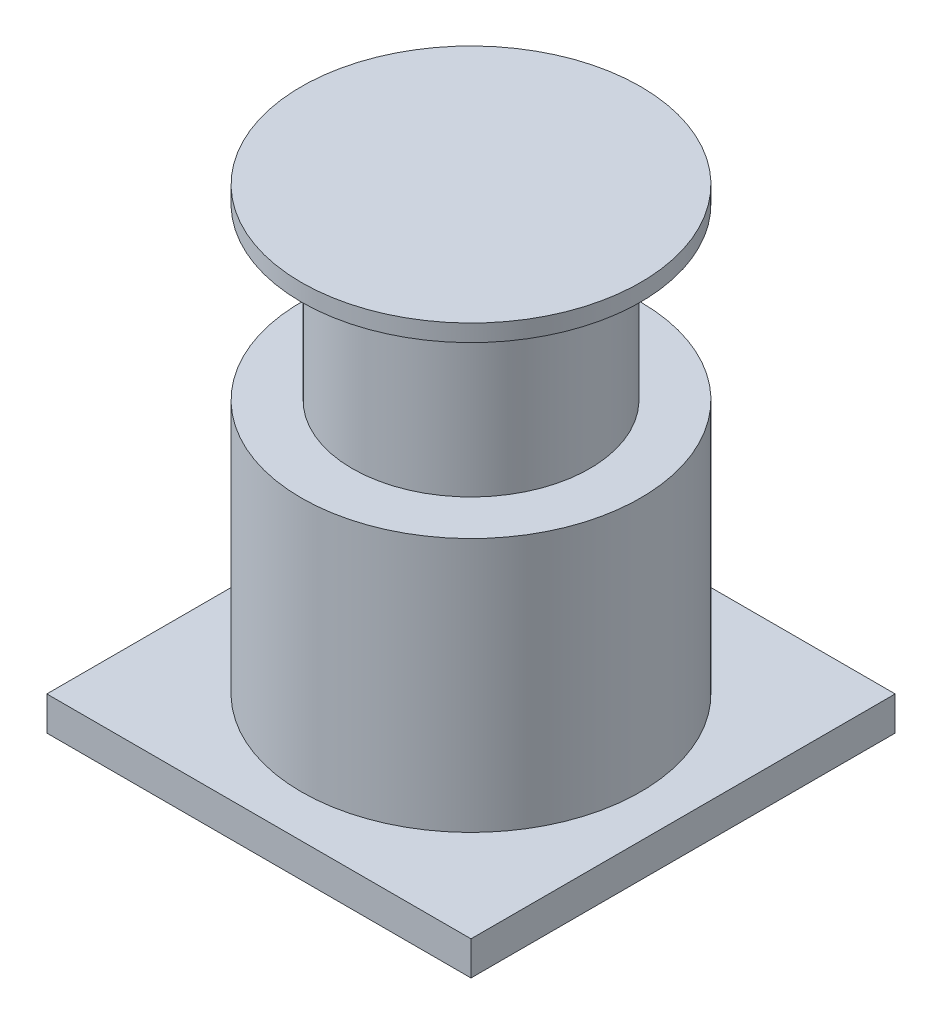
SolidWorks part; units mm, degrees
ref_plane "Front Plane" through (0, 0, 0) normal (0, 0, 1) x (1, 0, 0)
ref_plane "Top Plane" through (0, 0, 0) normal (0, 1, 0) x (1, 0, 0)
ref_plane "Right Plane" through (0, 0, 0) normal (1, 0, 0) x (0, 0, -1)
sketch "Sketch1" plane through (0, 0, 0) normal (0, 1, 0) x (1, 0, 0)
  line L1 (-78.1893, -163.1687) -> (171.8107, -163.1687)
  line L2 (-78.1893, -163.1687) -> (-78.1893, 86.8313)
  line L3 (-78.1893, 86.8313) -> (171.8107, 86.8313)
  line L4 (171.8107, -163.1687) -> (171.8107, 86.8313)
  dimension "D1" = 250
  dimension "D2" = 250
extrude "Boss-Extrude1" add sketch "Sketch1" along normal blind 20
sketch "Sketch2" plane through (0, 20, 0) normal (0, 1, 0) x (1, 0, 0)
  line L0 (171.8107, 86.8313) -> (-78.1893, 86.8313) construction
  line L1 (171.8107, -163.1687) -> (171.8107, 86.8313) construction
  circle A0 centre (46.8107, -38.1687) radius 100
  point P4 (46.8107, 86.8313)
  point P7 (171.8107, -38.1687)
  dimension "D1" = 200
extrude "Boss-Extrude2" add sketch "Sketch2" along normal blind 150
sketch "Sketch3" plane through (0, 170, 0) normal (0, 1, 0) x (1, 0, 0)
  circle A0 centre (46.8107, -38.1687) radius 70
  dimension "D1" = 140
extrude "Boss-Extrude3" add sketch "Sketch3" along normal blind 100
sketch "Sketch4" plane through (0, 270, 0) normal (0, 1, 0) x (1, 0, 0)
  circle A0 centre (46.8107, -38.1687) radius 100
extrude "Boss-Extrude4" add sketch "Sketch4" along normal blind 10
sketch "Sketch5" plane through (0, 0, 0) normal (0, -1, 0) x (1, 0, 0)
  line L0 (46.8107, 163.1687) -> (46.8107, -86.8313) construction
  line L1 (-78.1893, 163.1687) -> (171.8107, 163.1687) construction
  line L2 (171.8107, -86.8313) -> (-78.1893, -86.8313) construction
  line L3 (-78.1893, 38.1687) -> (171.8107, 38.1687) construction
  line L4 (-78.1893, -86.8313) -> (-78.1893, 163.1687) construction
  line L5 (171.8107, 163.1687) -> (171.8107, -86.8313) construction
  point P12 (46.8107, 38.1687)
